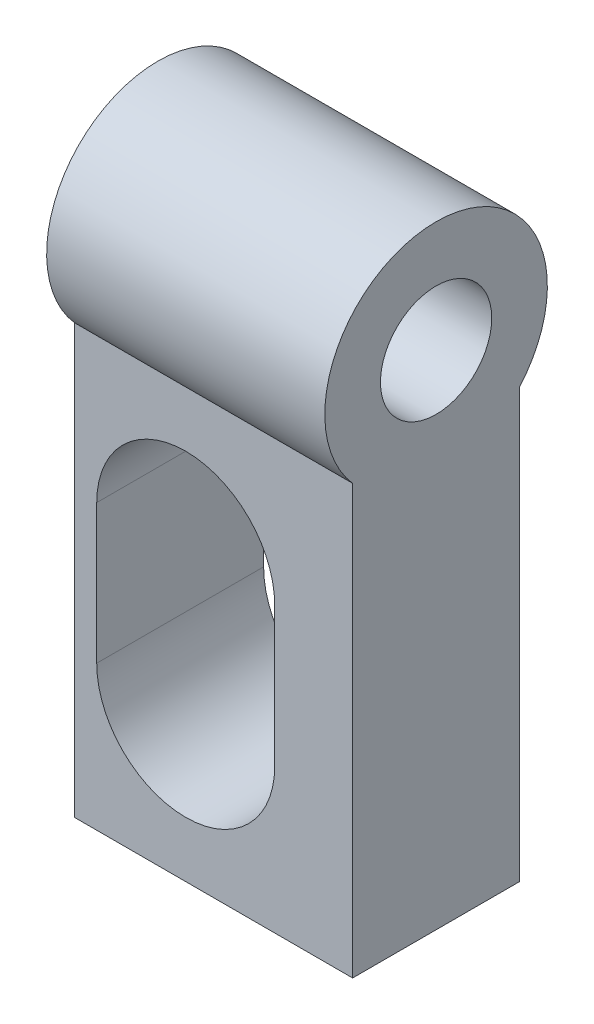
SolidWorks part; units mm, degrees
ref_plane "Front Plane" through (0, 0, 0) normal (0, 0, 1) x (1, 0, 0)
ref_plane "Top Plane" through (0, 0, 0) normal (0, 1, 0) x (1, 0, 0)
ref_plane "Right Plane" through (0, 0, 0) normal (1, 0, 0) x (0, 0, -1)
sketch "Sketch1" plane through (0, 0, 0) normal (1, 0, 0) x (0, 0, -1)
  line L0 (0, 7.7) -> (0, 0)
  line L1 (0, 0) -> (3, 0)
  line L2 (3, 0) -> (3, 7.7)
  circle A0 centre (1.5, 9.0229) radius 1
  arc A1 (0, 7.7) -> (3, 7.7) centre (1.5, 9.0229) cw
  dimension "D3" = 2
  dimension "D1" = 3
  dimension "D2" = 7.7
  dimension "D4" = 2
  dimension "D5" = 1.5
extrude "Boss-Extrude1" add sketch "Sketch1" along normal blind 5 contours A1 L0 L1 L2 A0
sketch "Sketch2" plane through (0, 0, -3) normal (0, 0, -1) x (-1, 0, 0)
  line L0 (-2, 5.1) -> (-2, 2.6) construction
  line L1 (-0.4, 5.1) -> (-0.4, 2.6)
  line L2 (-3.6, 5.1) -> (-3.6, 2.6)
  line L3 (0, 0) -> (0, 7.7) construction
  line L4 (-5, 0) -> (0, 0) construction
  arc A0 (-0.4, 5.1) -> (-3.6, 5.1) centre (-2, 5.1) ccw
  arc A1 (-3.6, 2.6) -> (-0.4, 2.6) centre (-2, 2.6) ccw
  point P2 (-2, 3.85)
  dimension "D1" = 1.6
  dimension "D2" = 2.5
  dimension "D3" = 2
  dimension "D4" = 3.85
extrude "Cut-Extrude1" cut sketch "Sketch2" against normal through all
